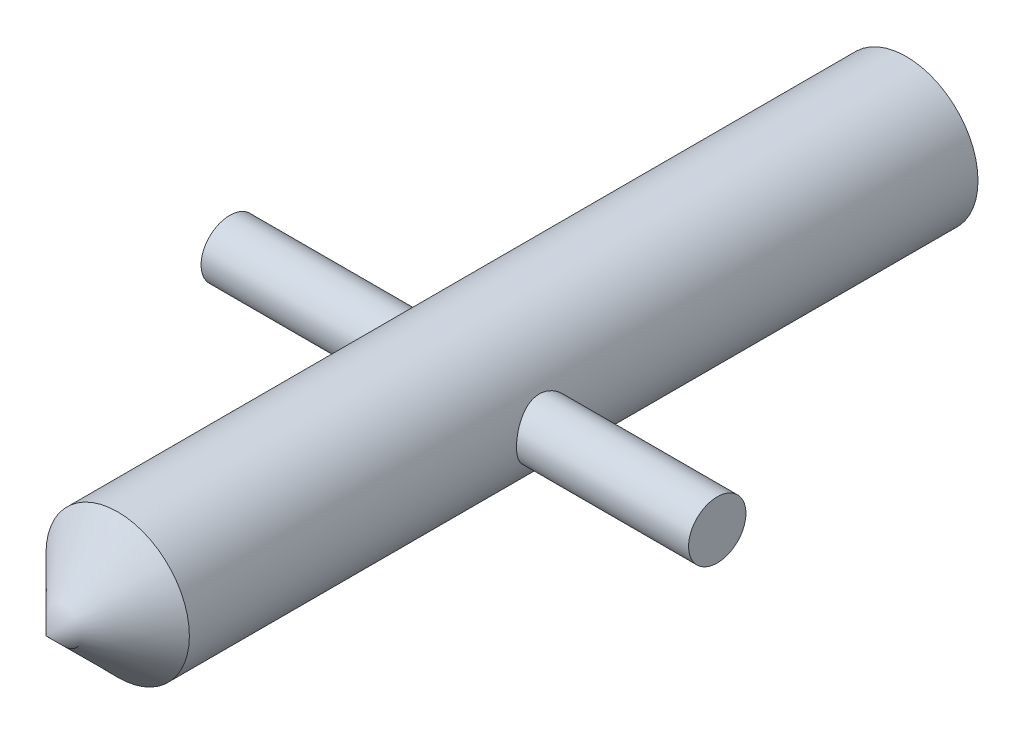
SolidWorks part; units mm, degrees
ref_plane "up基准面" through (0, 0, 0) normal (0, 0, 1) x (1, 0, 0)
ref_plane "前基准面" through (0, 0, 0) normal (0, 1, 0) x (1, 0, 0)
ref_plane "右视基准面" through (0, 0, 0) normal (1, 0, 0) x (0, 0, -1)
sketch "草图27" plane through (0, 0, 0) normal (0, 0, 1) x (1, 0, 0)
  circle A0 centre (0, 0) radius 5
extrude "凸台-拉伸14" add sketch "草图27" along normal blind 60
chamfer "倒角2" distance 5 angle 45 1 edges at (5, 0, 60)
sketch "草图29" plane through (0, 0, 0) normal (1, 0, 0) x (0, 0, -1)
  circle A0 centre (-30.1847, 0) radius 2
extrude "凸台-拉伸15" add sketch "草图29" along normal mid plane 34
